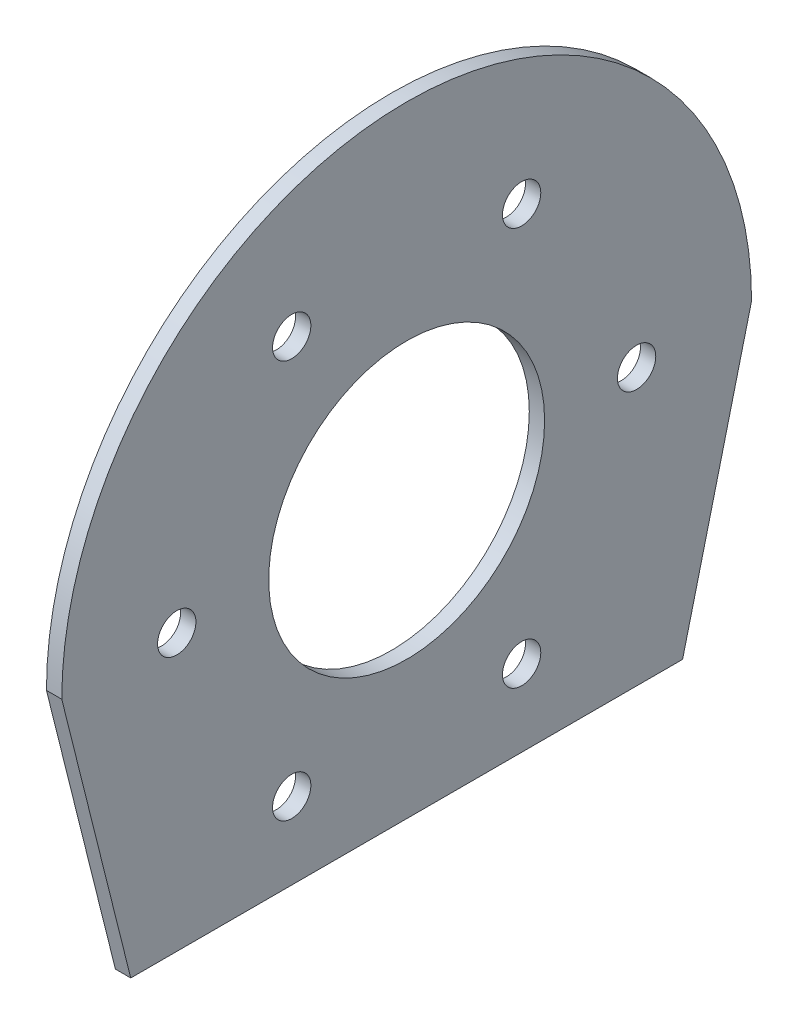
SolidWorks part; units mm, degrees
ref_plane "Front Plane" through (0, 0, 0) normal (0, 0, 1) x (1, 0, 0)
ref_plane "Top Plane" through (0, 0, 0) normal (0, 1, 0) x (1, 0, 0)
ref_plane "Right Plane" through (0, 0, 0) normal (1, 0, 0) x (0, 0, -1)
sketch "Sketch1" plane through (0, 0, 0) normal (1, 0, 0) x (0, 0, -1)
  line L0 (-22.5, 0) -> (22.5, 0) construction
  line L1 (0, 0) -> (0, -18) construction
  line L2 (-18, -18) -> (18, -18)
  line L3 (18, -18) -> (22.5, 0)
  line L4 (-18, -18) -> (-22.5, 0)
  circle A0 centre (0, 0) radius 9
  arc A1 (-22.5, 0) -> (22.5, 0) centre (0, 0) cw
  point P6 (0, 0)
  point P10 (0, -18)
  dimension "D1" = 18
  dimension "D2" = 45
  dimension "D3" = 18
  dimension "D4" = 36
extrude "Boss-Extrude1" add sketch "Sketch1" along normal mid plane 1
sketch "Sketch2" plane through (0.5, 0, 0) normal (1, 0, 0) x (0, 0, -1)
  line L0 (0, 0) -> (15, 0) construction
  circle A0 centre (0, 0) radius 15 construction
  circle A1 centre (15, 0) radius 1.25
  circle A2 centre (7.5, -12.9904) radius 1.25
  circle A3 centre (-7.5, -12.9904) radius 1.25
  circle A4 centre (-15, 0) radius 1.25
  circle A5 centre (-7.5, 12.9904) radius 1.25
  circle A6 centre (7.5, 12.9904) radius 1.25
  point P17 (0, 0)
  dimension "D1" = 30
  dimension "D2" = 2.5
  dimension "D3" = 6
extrude "Cut-Extrude1" cut sketch "Sketch2" against normal up to surface (1 mm away) up to face at (-0.5, -3.375, 0)
sketch "Sketch3" plane through (0.5, 0, 0) normal (1, 0, 0) x (0, 0, -1)
  line L0 (18, -18) -> (22.5, 0) construction
  line L1 (-18, -18) -> (18, -18) construction
  line L2 (-22.5, 0) -> (-18, -18) construction
  line L3 (18, -18) -> (22.5, 0)
  line L4 (-18, -18) -> (18, -18)
  line L5 (-22.5, 0) -> (-18, -18)
  arc A0 (22.5, 0) -> (-22.5, 0) centre (0, 0) ccw construction
  arc A1 (22.5, 0) -> (-22.5, 0) centre (0, 0) ccw
  circle A2 centre (7.5, 12.9904) radius 1.25 construction
  circle A3 centre (15, 0) radius 1.25 construction
  circle A4 centre (7.5, -12.9904) radius 1.25 construction
  circle A5 centre (-7.5, -12.9904) radius 1.25 construction
  circle A6 centre (-15, 0) radius 1.25 construction
  circle A7 centre (-7.5, 12.9904) radius 1.25 construction
  circle A8 centre (7.5, 12.9904) radius 1.25 construction
  circle A9 centre (15, 0) radius 1.25 construction
  circle A10 centre (7.5, -12.9904) radius 1.25 construction
  circle A11 centre (-7.5, -12.9904) radius 1.25 construction
  circle A12 centre (-15, 0) radius 1.25 construction
  circle A13 centre (-7.5, 12.9904) radius 1.25 construction
